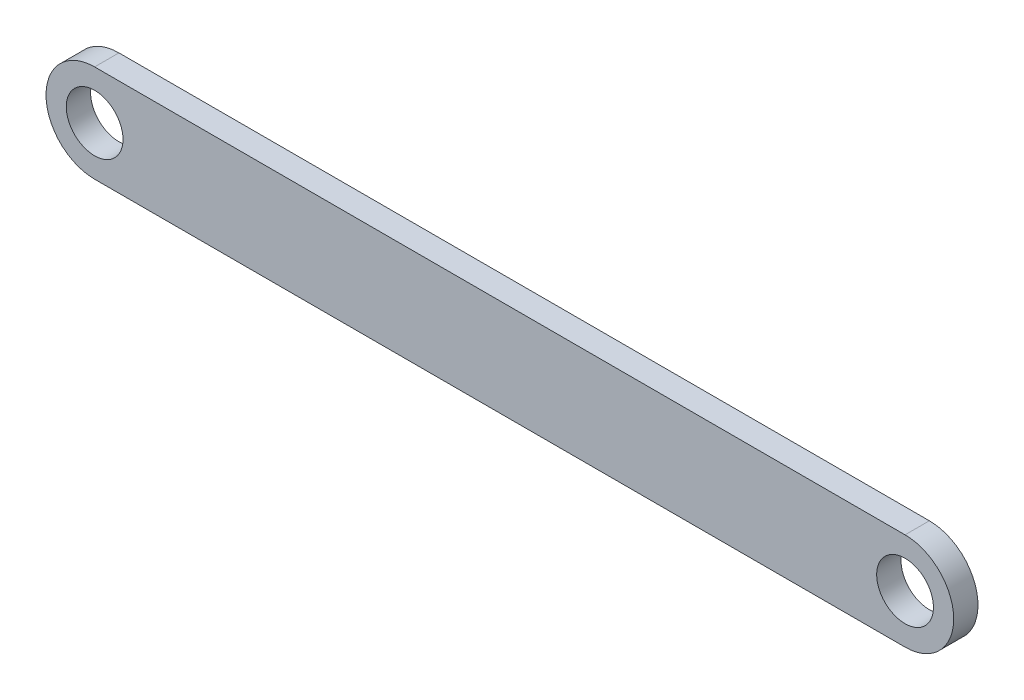
SolidWorks part; units mm, degrees
ref_plane "Ön Düzlem" through (0, 0, 0) normal (0, 0, 1) x (1, 0, 0)
ref_plane "Üst Düzlem" through (0, 0, 0) normal (0, 1, 0) x (1, 0, 0)
ref_plane "Sağ Düzlem" through (0, 0, 0) normal (1, 0, 0) x (0, 0, -1)
sketch "Çizim1" plane through (0, 0, 0) normal (0, 0, 1) x (1, 0, 0)
  line L0 (-50, 0) -> (50, 0) construction
  line L1 (-50, 6) -> (50, 6)
  line L2 (-50, -6) -> (50, -6)
  arc A0 (-50, 6) -> (-50, -6) centre (-50, 0) ccw
  arc A1 (50, -6) -> (50, 6) centre (50, 0) ccw
  circle A2 centre (50, 0) radius 3.5
  circle A3 centre (-50, 0) radius 3.5
  point P3 (0, 0)
  dimension "D1" = 6
  dimension "D3" = 7
  dimension "D4" = 7
  dimension "D2" = 100
extrude "Yükseklik-Ekstrüzyon1" add sketch "Çizim1" along normal blind 3
